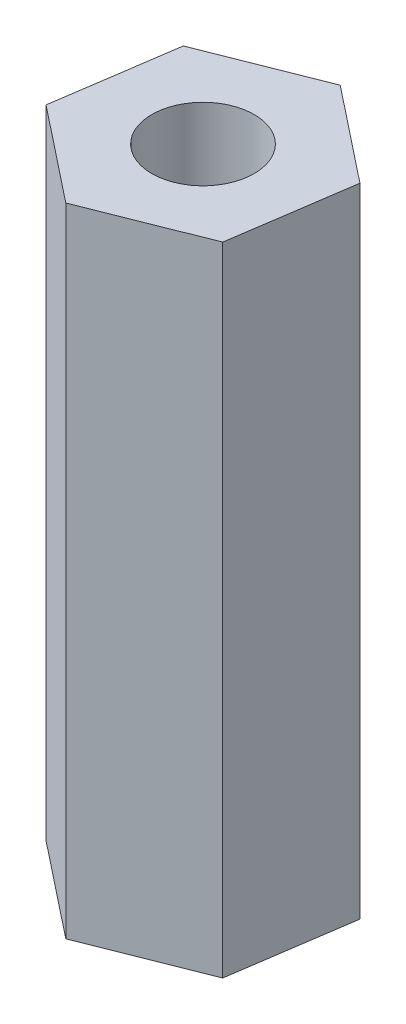
SolidWorks part; units mm, degrees
ref_plane "Alzado" through (0, 0, 0) normal (0, 0, 1) x (1, 0, 0)
ref_plane "Planta" through (0, 0, 0) normal (0, 1, 0) x (1, 0, 0)
ref_plane "Vista lateral" through (0, 0, 0) normal (1, 0, 0) x (0, 0, -1)
sketch "Croquis base" plane through (0, 0, 0) normal (0, 1, 0) x (1, 0, 0)
  line L1 (2.0823, -1.6485) -> (2.4688, 0.9791)
  line L2 (2.4688, 0.9791) -> (0.3865, 2.6275)
  line L3 (0.3865, 2.6275) -> (-2.0823, 1.6485)
  line L4 (-2.0823, 1.6485) -> (-2.4688, -0.9791)
  line L5 (-2.4688, -0.9791) -> (-0.3865, -2.6275)
  line L6 (-0.3865, -2.6275) -> (2.0823, -1.6485)
  circle A0 centre (0, 0) radius 2.3 construction
extrude "Saliente-Extruir1" add sketch "Croquis base" along normal blind 14
sketch "Croquis cara" plane through (0, 14, 0) normal (0, 1, 0) x (1, 0, 0)
  circle A0 centre (0, 0) radius 1.125
extrude "Cortar-Extruir1" cut sketch "Croquis cara" against normal through all
